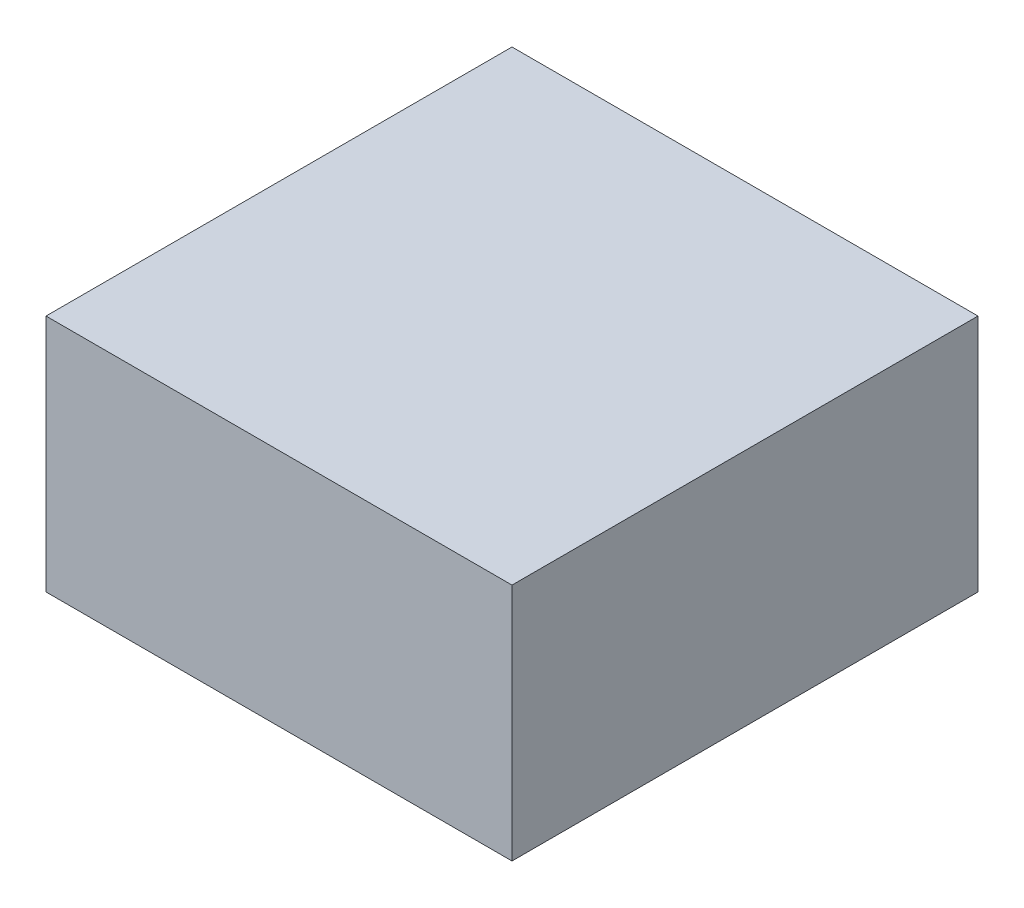
SolidWorks part; units mm, degrees
ref_plane "Front Plane" through (0, 0, 0) normal (0, 0, 1) x (1, 0, 0)
ref_plane "Top Plane" through (0, 0, 0) normal (0, 1, 0) x (1, 0, 0)
ref_plane "Right Plane" through (0, 0, 0) normal (1, 0, 0) x (0, 0, -1)
sketch "Sketch1" plane through (0, 0, 0) normal (0, 1, 0) x (1, 0, 0)
  line L1 (-3.5843, 3.1571) -> (4.2157, 3.1571)
  line L2 (-3.5843, 3.1571) -> (-3.5843, -4.6429)
  line L3 (-3.5843, -4.6429) -> (4.2157, -4.6429)
  line L4 (4.2157, 3.1571) -> (4.2157, -4.6429)
  dimension "D1" = 7.8
  dimension "D2" = 7.8
extrude "Boss-Extrude1" add sketch "Sketch1" along normal blind 3
sketch "Sketch3" plane through (0, 3, 0) normal (0, 1, 0) x (1, 0, 0)
  line L4 (-3.5843, 3.1571) -> (-3.5843, -4.6429)
  line L5 (-3.5843, -4.6429) -> (4.2157, -4.6429)
  line L6 (4.2157, -4.6429) -> (4.2157, 3.1571)
  line L7 (4.2157, 3.1571) -> (-3.5843, 3.1571)
  line L8 (-3.5843, 3.1571) -> (-3.5843, -4.6429)
  line L9 (-3.5843, -4.6429) -> (4.2157, -4.6429)
  line L10 (4.2157, -4.6429) -> (4.2157, 3.1571)
  line L11 (4.2157, 3.1571) -> (-3.5843, 3.1571)
  dimension "D1" = 0
extrude "Boss-Extrude2" add sketch "Sketch3" along normal blind 1
sketch "Sketch4" plane through (0, 0, 0) normal (0, -1, 0) x (1, 0, 0)
  line L3 (0.3194, 2.2422) -> (1.8187, 2.2422)
  line L4 (1.8187, 2.2422) -> (1.8187, -0.7564)
  line L5 (1.8187, -0.7564) -> (-1.1799, -0.7564)
  line L6 (-1.1799, -0.7564) -> (-1.1799, 2.2422)
  line L7 (-1.1799, 2.2422) -> (0.3194, 2.2422)
extrude "Cut-Extrude1" cut sketch "Sketch4" against normal blind 3
